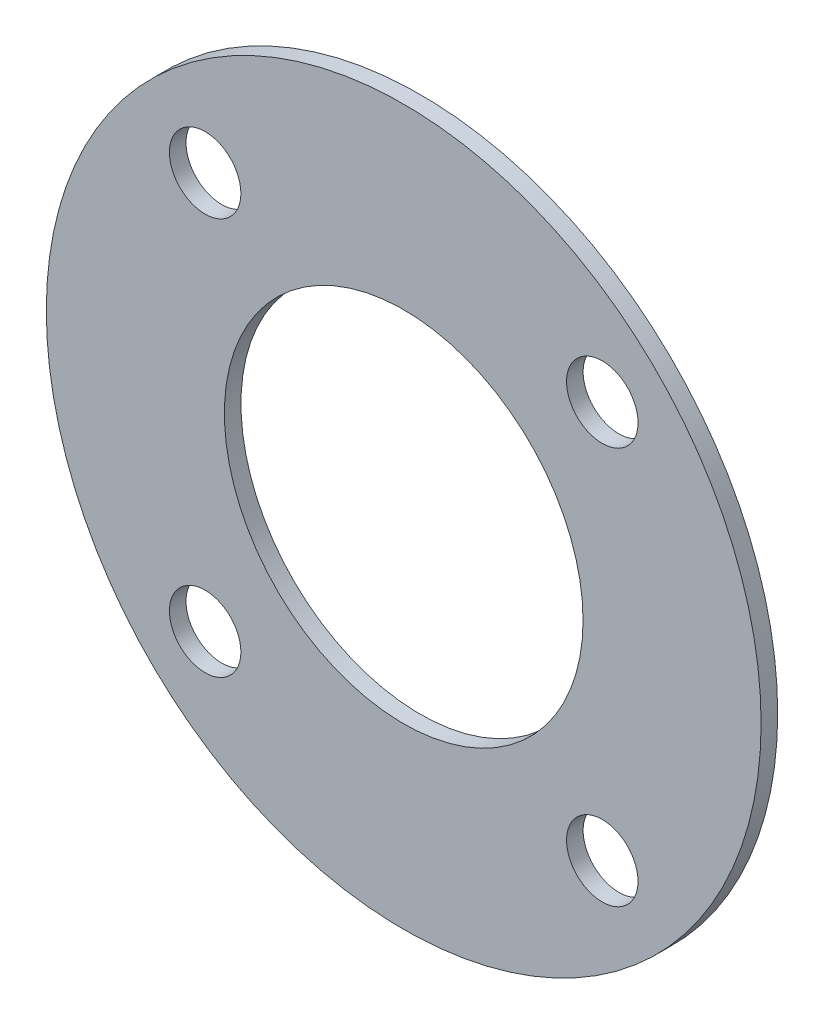
SolidWorks part; units mm, degrees
material "6061-T6 (SS)"
ref_plane "Front Plane" through (0, 0, 0) normal (0, 0, 1) x (1, 0, 0)
ref_plane "Top Plane" through (0, 0, 0) normal (0, 1, 0) x (1, 0, 0)
ref_plane "Right Plane" through (0, 0, 0) normal (1, 0, 0) x (0, 0, -1)
sketch "Sketch1" plane through (0, 0, 0) normal (0, 0, 1) x (1, 0, 0)
  circle A0 centre (0, 0) radius 14
  circle A1 centre (0, 0) radius 7.025
extrude "Hub_Endplate_Axial_Clearance_Shim_H0p65" add sketch "Sketch1" along normal blind 0.65 from offset 3
sketch "Sketch2" plane through (0, 0, 3.65) normal (0, 0, 1) x (1, 0, 0)
  circle A0 centre (7.7782, 7.7782) radius 1.4
  circle A1 centre (-7.7782, 7.7782) radius 1.4
  circle A2 centre (-7.7782, -7.7782) radius 1.4
  circle A3 centre (7.7782, -7.7782) radius 1.4
extrude "Four_D2p8_PCD22" cut sketch "Sketch2" against normal through all
